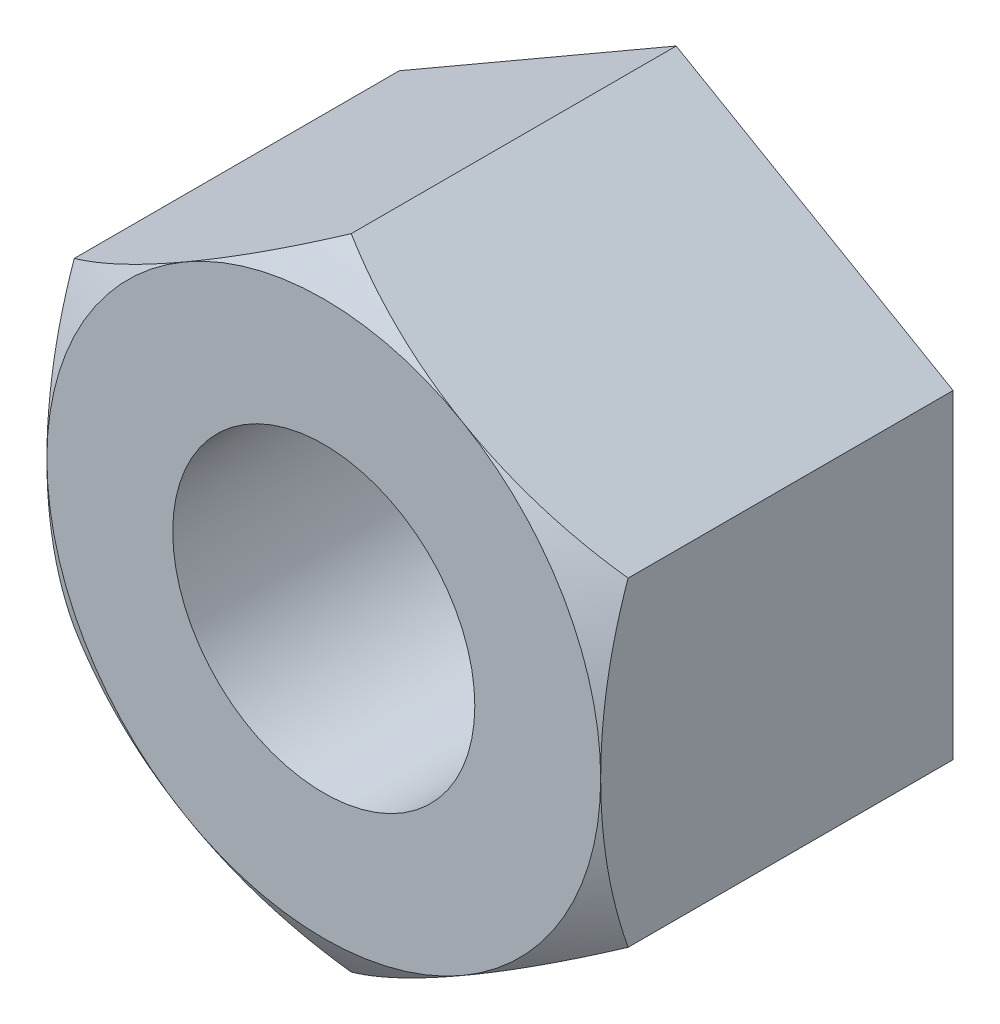
SolidWorks part; units mm, degrees
material "炭素鋼(普通)"
ref_plane "正面" through (0, 0, 0) normal (0, 0, 1) x (1, 0, 0)
ref_plane "平面" through (0, 0, 0) normal (0, 1, 0) x (1, 0, 0)
ref_plane "右側面" through (0, 0, 0) normal (1, 0, 0) x (0, 0, -1)
sketch "ｽｹｯﾁ1" plane through (0, 0, 0) normal (0, 0, 1) x (1, 0, 0)
  line L1 (0, 3.1754) -> (-2.75, 1.5877)
  line L2 (-2.75, 1.5877) -> (-2.75, -1.5877)
  line L3 (-2.75, -1.5877) -> (0, -3.1754)
  line L4 (0, -3.1754) -> (2.75, -1.5877)
  line L5 (2.75, -1.5877) -> (2.75, 1.5877)
  line L6 (2.75, 1.5877) -> (0, 3.1754)
  circle A0 centre (0, 0) radius 2.75 construction
  circle A1 centre (0, 0) radius 1.5
  dimension "D2" = 3
  dimension "D1" = 5.5
extrude "ﾎﾞｽ - 押し出し1" add sketch "ｽｹｯﾁ1" along normal blind 3.5
sketch "ｽｹｯﾁ4" plane through (0, 0, 3.5) normal (0, 0, 1) x (1, 0, 0)
  line L0 (0, 3.1754) -> (-2.75, 1.5877) construction
  circle A0 centre (0, 0) radius 2.75
sketch "ｽｹｯﾁ5" plane through (0, 0, 0) normal (1, 0, 0) x (0, 0, -1)
  line L0 (-3.5, 2.75) -> (-3.5, -2.75) construction
  line L1 (-3.5, 1.5877) -> (-3.5, 3.1754) construction
  line L2 (-3.5, 3.1754) -> (0, 3.1754) construction
  line L3 (0, 0) -> (-3.5, 0) construction
  line L4 (0, -1.5877) -> (0, 1.5877) construction
  line L5 (-3.2276, 3.1754) -> (-3.5, 3.1754)
  line L6 (-3.5, 3.1754) -> (-3.5, 2.75)
  line L7 (-3.5, 2.75) -> (-3.2544, 3.1754) construction
  arc A0 (-3.5, 2.75) -> (-3.2276, 3.1754) centre (1.2631, 0) cw
  dimension "D1" = 30
revolve "ｶｯﾄ - 回転2" cut sketch "ｽｹｯﾁ5" angle 360 about L3
